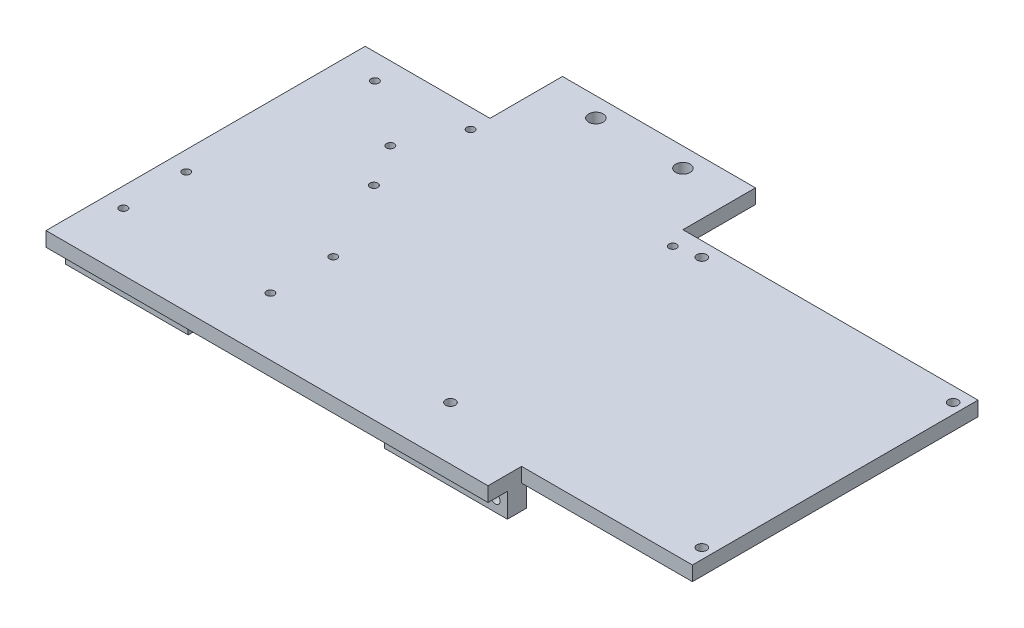
SolidWorks part; units mm, degrees
ref_plane "Front Plane" through (0, 0, 0) normal (0, 0, 1) x (1, 0, 0)
ref_plane "Top Plane" through (0, 0, 0) normal (0, 1, 0) x (1, 0, 0)
ref_plane "Right Plane" through (0, 0, 0) normal (1, 0, 0) x (0, 0, -1)
sketch "Sketch1" plane through (0, 0, 0) normal (0, 1, 0) x (1, 0, 0)
  line L1 (0, 0) -> (116.078, 0)
  line L2 (0, 0) -> (0, 102.87)
  line L3 (0, 102.87) -> (116.078, 102.87)
  line L4 (116.078, 0) -> (116.078, 102.87)
  dimension "D1" = 102.87
  dimension "D2" = 116.078
extrude "Boss-Extrude1" add sketch "Sketch1" along normal blind 3.81
sketch "Sketch2" plane through (0, 3.81, 0) normal (0, 1, 0) x (1, 0, 0)
  line L0 (116.078, 102.87) -> (0, 102.87) construction
  line L1 (0, 102.87) -> (32.766, 102.87)
  line L2 (0, 102.87) -> (0, 83.82)
  line L3 (0, 83.82) -> (32.766, 83.82)
  line L4 (32.766, 102.87) -> (32.766, 83.82)
  line L5 (116.078, 102.87) -> (83.439, 102.87)
  line L6 (116.078, 102.87) -> (116.078, 83.82)
  line L7 (116.078, 83.82) -> (83.439, 83.82)
  line L8 (83.439, 102.87) -> (83.439, 83.82)
  circle A0 centre (46.609, 97.79) radius 1.905
  circle A1 centre (69.469, 97.79) radius 1.905
  point P14 (58.039, 102.87)
  point P17 (58.039, 102.87)
  dimension "D5" = 11.43
  dimension "D8" = 3.81
  dimension "D10" = 3.81
  dimension "D1" = 19.05
  dimension "D2" = 19.05
  dimension "D3" = 32.639
  dimension "D4" = 32.766
  dimension "D6" = 11.43
  dimension "D7" = 5.08
  dimension "D9" = 5.08
extrude "Cut-Extrude1" cut sketch "Sketch2" against normal up to surface (3.81 mm away) up to face at (58.039, 0, -51.435)
sketch "Sketch3" plane through (0, 0, 0) normal (0, -1, 0) x (1, 0, 0)
  line L0 (0, -83.82) -> (0, 0) construction
  line L1 (0, -5.08) -> (32.258, -5.08)
  line L2 (0, -5.08) -> (0, -10.16)
  line L3 (0, -10.16) -> (32.258, -10.16)
  line L4 (32.258, -5.08) -> (32.258, -10.16)
  line L5 (116.078, 0) -> (116.078, -83.82) construction
  line L6 (116.078, -5.08) -> (83.82, -5.08)
  line L7 (116.078, -5.08) -> (116.078, -10.16)
  line L8 (116.078, -10.16) -> (83.82, -10.16)
  line L9 (83.82, -5.08) -> (83.82, -10.16)
  line L10 (0, 0) -> (116.078, 0) construction
  dimension "D1" = 5.08
  dimension "D2" = 5.08
  dimension "D3" = 32.258
extrude "Boss-Extrude2" add sketch "Sketch3" along normal blind 6.35
sketch "Sketch4" plane through (0, 0, -5.08) normal (0, 0, 1) x (1, 0, 0)
  line L0 (0, -6.35) -> (0, 0) construction
  line L1 (32.258, -6.35) -> (0, -6.35) construction
  line L2 (116.078, -6.35) -> (116.078, 0) construction
  circle A0 centre (3.175, -3.175) radius 1.27
  circle A1 centre (11.811, -3.175) radius 1.27
  circle A2 centre (20.447, -3.175) radius 1.27
  circle A3 centre (29.083, -3.175) radius 1.27
  circle A4 centre (86.995, -3.175) radius 1.27
  circle A5 centre (95.631, -3.175) radius 1.27
  circle A6 centre (104.267, -3.175) radius 1.27
  circle A7 centre (112.903, -3.175) radius 1.27
  dimension "D1" = 2.54
  dimension "D2" = 8.636
  dimension "D3" = 8.636
  dimension "D4" = 8.636
  dimension "D5" = 3.175
  dimension "D6" = 3.175
  dimension "D7" = 3.175
  dimension "D8" = 8.636
  dimension "D9" = 8.636
  dimension "D10" = 8.636
extrude "Cut-Extrude2" cut sketch "Sketch4" against normal up to surface (5.08 mm away) up to face at (12.0968, -3.9688, -10.16)
sketch "Sketch5" plane through (0, 3.81, 0) normal (0, 1, 0) x (1, 0, 0)
  line L0 (0, 83.82) -> (32.766, 83.82) construction
  line L1 (0, 83.82) -> (0, 0) construction
  line L3 (0, 10.16) -> (32.258, 10.16) construction
  circle A0 centre (25.908, 64.516) radius 1.016
  circle A1 centre (9.144, 77.216) radius 1.016
  circle A2 centre (32.766, 78.74) radius 1.016
  circle A3 centre (85.852, 78.74) radius 1.016
  circle A4 centre (32.766, 53.34) radius 1.016
  circle A5 centre (5.08, 31.75) radius 1.016
  circle A6 centre (43.688, 31.75) radius 1.016
  circle A7 centre (5.08, 15.24) radius 1.016
  circle A8 centre (43.688, 15.24) radius 1.016
  dimension "D1" = 6.604
  dimension "D2" = 9.144
  dimension "D4" = 25.908
  dimension "D5" = 2.032
  dimension "D6" = 25.4
  dimension "D7" = 53.086
  dimension "D8" = 2.032
  dimension "D9" = 0
  dimension "D13" = 2.032
  dimension "D14" = 5.08
  dimension "D15" = 5.08
  dimension "D3" = 19.304
  dimension "D10" = 5.08
  dimension "D11" = 38.608
  dimension "D12" = 16.51
extrude "Cut-Extrude4" cut sketch "Sketch5" against normal up to surface (3.81 mm away) up to face at (46.609, 0, -99.695)
sketch "Sketch6" plane through (0, 3.81, 0) normal (0, 1, 0) x (1, 0, 0)
  line L0 (83.439, 83.82) -> (116.078, 83.82) construction
  line L1 (90.932, 83.82) -> (160.932, 83.82)
  line L2 (90.932, 83.82) -> (90.932, 8.82)
  line L3 (90.932, 8.82) -> (160.932, 8.82)
  line L4 (160.932, 83.82) -> (160.932, 8.82)
  circle A0 centre (85.852, 78.74) radius 1.016 construction
  dimension "D4" = 5.08
  dimension "D1" = 70
  dimension "D2" = 75
  dimension "D3" = 0
extrude "Boss-Extrude3" add sketch "Sketch6" against normal up to surface (3.81 mm away) up to face at (43.688, 0, -16.256)
sketch "Sketch7" plane through (0, 3.81, 0) normal (0, 1, 0) x (1, 0, 0)
  line L2 (83.439, 83.82) -> (160.932, 83.82) construction
  circle A0 centre (92.202, 14.01) radius 1.27
  circle A1 centre (92.202, 80.01) radius 1.27
  circle A2 centre (158.202, 80.01) radius 1.27
  circle A3 centre (158.202, 14.01) radius 1.27
  circle A4 centre (85.852, 78.74) radius 1.016 construction
  dimension "D1" = 66
  dimension "D3" = 2.54
  dimension "D4" = 6.35
  dimension "D5" = 3.81
  dimension "D2" = 66
extrude "Cut-Extrude5" cut sketch "Sketch7" against normal up to surface (3.81 mm away) up to face at (69.4857, 0, -36.6106)
